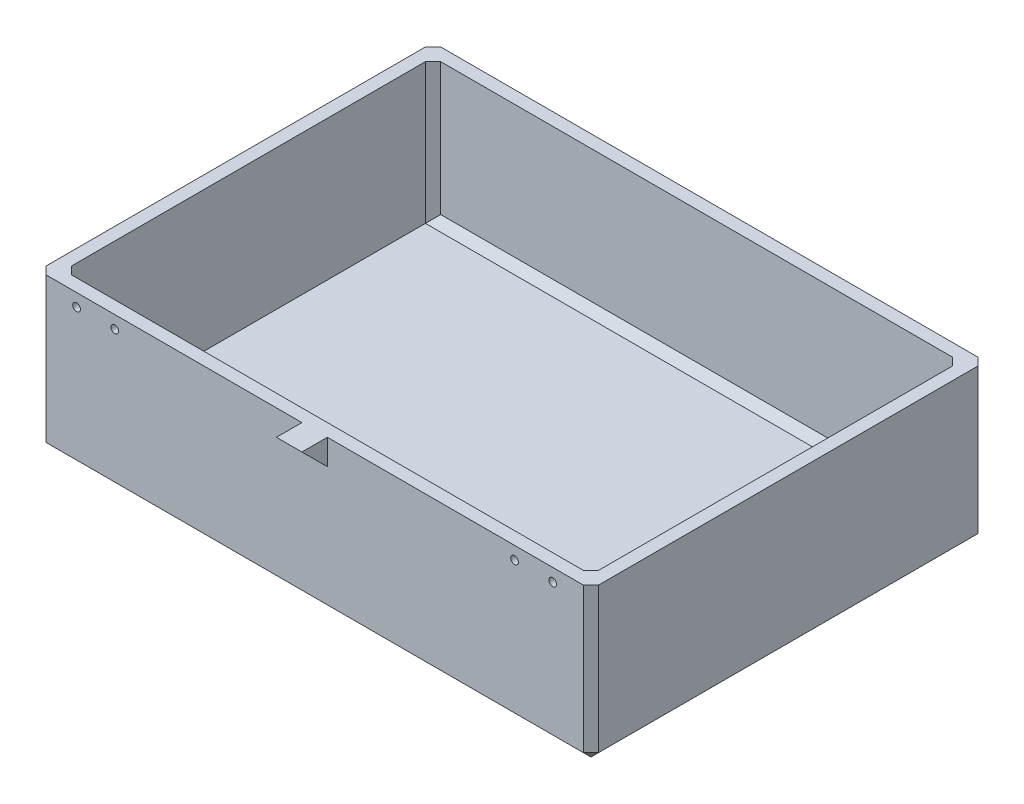
SolidWorks part; units mm, degrees
ref_plane "Vorne" through (0, 0, 0) normal (0, 0, 1) x (1, 0, 0)
ref_plane "Oben" through (0, 0, 0) normal (0, 1, 0) x (1, 0, 0)
ref_plane "Rechts" through (0, 0, 0) normal (1, 0, 0) x (0, 0, -1)
sketch "Skizze2" plane through (0, 0, 0) normal (0, 1, 0) x (1, 0, 0)
  line L1 (-108.5, 77.5) -> (108.5, 77.5)
  line L2 (-108.5, 77.5) -> (-108.5, -77.5)
  line L3 (-108.5, -77.5) -> (108.5, -77.5)
  line L4 (108.5, 77.5) -> (108.5, -77.5)
  line L5 (-108.5, 77.5) -> (108.5, -77.5) construction
  line L6 (-108.5, -77.5) -> (108.5, 77.5) construction
  point P0 (0, 0)
  dimension "D1" = 217
  dimension "D2" = 155
extrude "Aufsatz-Linear austragen1" add sketch "Skizze2" along normal blind 60
shell "Wandung1" thickness 5
sketch "Skizze7" plane through (0, 0, 77.5) normal (0, 0, 1) x (1, 0, 0)
  line L1 (-108.5, 60) -> (-108.5, 0) construction
  line L2 (-108.5, 60) -> (108.5, 60) construction
  line L3 (0, -55) -> (0, 55) construction
  circle A0 centre (-93.5, 55) radius 1.5
  circle A2 centre (-78.5, 55) radius 1.5
  circle A4 centre (78.5, 55) radius 1.5
  circle A5 centre (93.5, 55) radius 1.5
  dimension "D1" = 3
  dimension "D2" = 3
  dimension "D3" = 5
  dimension "D4" = 5
  dimension "D5" = 15
  dimension "D6" = 15
extrude "Schnitt-Linear austragen1" cut sketch "Skizze7" against normal up to next
sketch "Skizze8" plane through (0, 0, 77.5) normal (0, 0, 1) x (1, 0, 0)
  line L0 (-108.5, 60) -> (108.5, 60) construction
  line L1 (5, 60) -> (-5, 60)
  line L2 (5, 60) -> (5, 50)
  line L3 (5, 50) -> (-5, 50)
  line L4 (-5, 60) -> (-5, 50)
  line L5 (5, 60) -> (-5, 50) construction
  line L6 (5, 50) -> (-5, 60) construction
  point P0 (0, 55)
  dimension "D1" = 10
  dimension "D2" = 10
  dimension "D3" = 0
  dimension "D4" = 0
extrude "Aufsatz-Linear austragen2" add sketch "Skizze8" along normal blind 10
sketch "Skizze9" plane through (-5, 0, 0) normal (-1, 0, 0) x (0, 0, 1)
  line L0 (77.5, 50) -> (87.5, 60)
  line L1 (87.5, 60) -> (87.5, 50)
  line L2 (87.5, 50) -> (77.5, 50)
extrude "Schnitt-Linear austragen2" cut sketch "Skizze9" against normal up to next
chamfer "Fase1" distance 3 angle 45 14 edges at (-103.5, 32.5, 72.5) (-103.5, 32.5, -72.5) (103.5, 32.5, 72.5) (103.5, 32.5, -72.5) (0, 5, -72.5) (103.5, 5, 0) (0, 0, -77.5) (108.5, 30, -77.5) (108.5, 0, 0) (108.5, 30, 77.5) (0, 0, 77.5) (-108.5, 30, 77.5) (-108.5, 0, 0) (-108.5, 30, -77.5)
